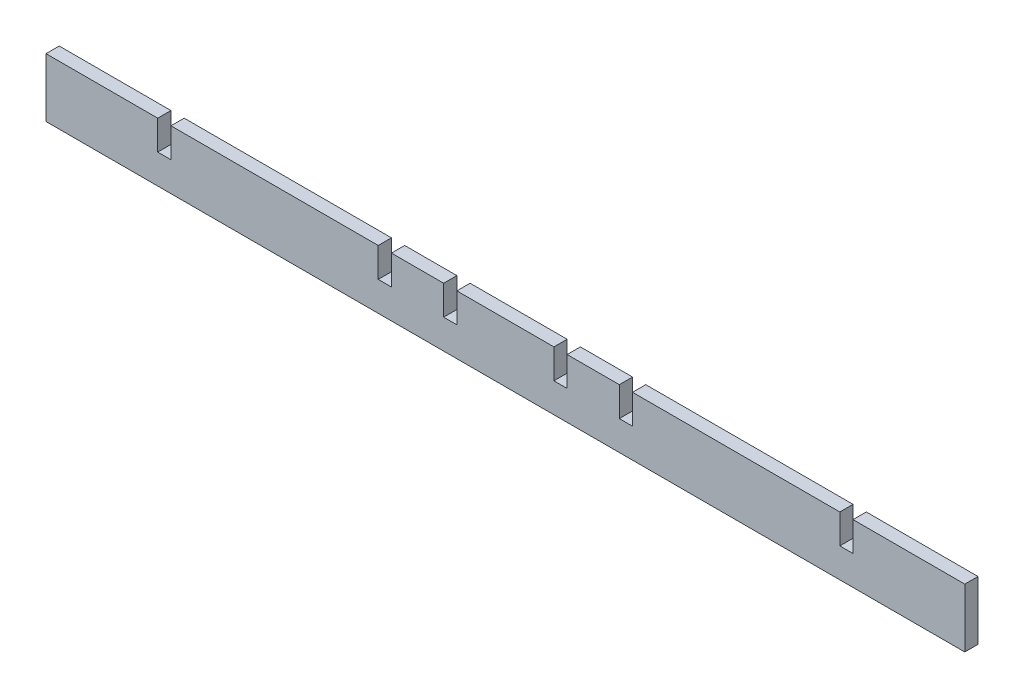
SolidWorks part; units mm, degrees
ref_plane "Front Plane" through (0, 0, 0) normal (0, 0, 1) x (1, 0, 0)
ref_plane "Top Plane" through (0, 0, 0) normal (0, 1, 0) x (1, 0, 0)
ref_plane "Right Plane" through (0, 0, 0) normal (1, 0, 0) x (0, 0, -1)
sketch "Sketch1" plane through (0, 0, 0) normal (0, 0, 1) x (1, 0, 0)
  line L0 (0, 0) -> (0, 29.1506) construction
  line L1 (-625, -40) -> (625, -40)
  line L2 (-625, -40) -> (-625, 40)
  line L3 (-625, 40) -> (625, 40)
  line L4 (625, -40) -> (625, 40)
  line L5 (-625, -40) -> (625, 40) construction
  line L6 (-625, 40) -> (625, -40) construction
  line L7 (-625, 0) -> (625, 0) construction
  line L8 (150, 25.3608) -> (150, -10.0427) construction
  line L9 (-150, -10.0427) -> (-150, 25.3608) construction
  line L10 (-155, 40) -> (-155, 0)
  line L11 (-155, 0) -> (-173, 0)
  line L12 (-173, 0) -> (-173, 40)
  line L13 (-66, 40) -> (-66, 0)
  line L14 (-66, 0) -> (-84, 0)
  line L15 (-84, 0) -> (-84, 40)
  line L16 (66, 40) -> (66, 0)
  line L17 (66, 0) -> (84, 0)
  line L18 (84, 0) -> (84, 40)
  line L19 (-75, 0) -> (-75, 40) construction
  line L20 (75, 0) -> (75, 40) construction
  line L21 (155, 40) -> (155, 0)
  line L22 (155, 0) -> (173, 0)
  line L23 (173, 0) -> (173, 40)
  line L24 (-455, 40) -> (-455, 0)
  line L25 (-455, 0) -> (-473, 0)
  line L26 (-473, 0) -> (-473, 40)
  line L27 (455, 40) -> (455, 0)
  line L28 (455, 0) -> (473, 0)
  line L29 (473, 0) -> (473, 40)
  point P0 (0, 0)
  point P37 (-173, 20)
  dimension "D1" = 1250
  dimension "D2" = 80
  dimension "D3" = 150
  dimension "D4" = 150
  dimension "D5" = 18
  dimension "D6" = 5
  dimension "D7" = 75
  dimension "D8" = 75
  dimension "D9" = 300
  dimension "D10" = 5
  dimension "D11" = 300
extrude "Boss-Extrude1" add sketch "Sketch1" along normal blind 18 contours L29 L28 L27 L3 L23 L22 L21 L18 L17 L16 L13 L14 L15 L10 L11 L12 L24 L25 L26 L2 L1 L4
